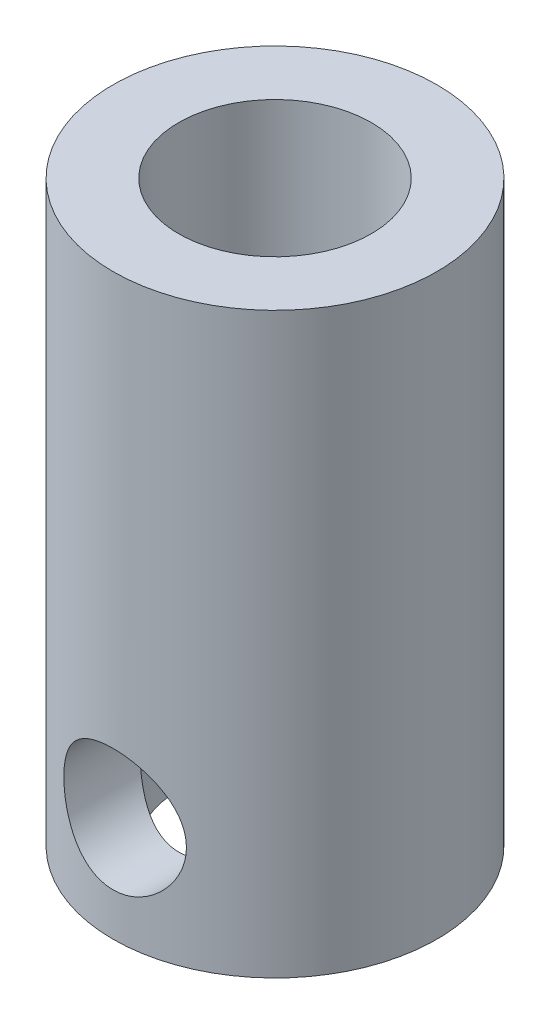
SolidWorks part; units mm, degrees
ref_plane "Front Plane" through (0, 0, 0) normal (0, 0, 1) x (1, 0, 0)
ref_plane "Top Plane" through (0, 0, 0) normal (0, 1, 0) x (1, 0, 0)
ref_plane "Right Plane" through (0, 0, 0) normal (1, 0, 0) x (0, 0, -1)
sketch "Sketch1" plane through (0, 0, 0) normal (0, 0, 1) x (1, 0, 0)
  line L0 (5.334, 19.05) -> (0, 19.05)
  line L1 (0, 19.05) -> (0, 0)
  line L2 (0, 0) -> (5.334, 0)
  line L3 (5.334, 0) -> (5.334, 19.05)
  line L4 (0, 19.05) -> (0, 0) construction
revolve "Revolve1" add sketch "Sketch1" angle 360 about L4
hole_wizard "1/4 (0.25) Diameter Hole1" positions "Sketch3" profile "Sketch2" hole size "1/4" standard "ANSI Inch"
sketch "Sketch3" plane through (0, 0, 0) normal (0, -1, 0) x (-1, 0, 0)
  point P0 (0, 0)
sketch "Sketch2" plane through (0, 0, 0) normal (1, 0, 0) x (0, 0, -1)
  line L0 (0, 0) -> (0, 19.05)
  line L1 (0, 19.05) -> (3.175, 19.05)
  line L2 (3.175, 19.05) -> (3.175, 0)
  line L5 (3.175, 0) -> (0, 0)
  line L11 (0, -6.35) -> (0, 107.95) construction
  dimension "Thru Hole Dia." = 6.35
  dimension "Thru Hole Depth" = 19.05
hole_wizard "#21 (0.159) Diameter Hole1" positions "3DSketch1" profile "Sketch4" hole size "#21" standard "ANSI Inch"
sketch3d "3DSketch1"
  point P0 (0, 3.429, 5.334)
  point P1 (0, 15.621, 5.334)
sketch "Sketch4" plane through (0, 3.429, 5.334) normal (1, 0, 0) x (0, -1, 0)
  line L0 (0, 0) -> (0, 2.159)
  line L1 (0, 2.159) -> (2.0193, 2.159)
  line L2 (2.0193, 2.159) -> (2.0193, 0)
  line L5 (2.0193, 0) -> (0, 0)
  line L11 (0, -6.35) -> (0, 107.95) construction
  dimension "Thru Hole Dia." = 4.0386
  dimension "Thru Hole Depth" = 2.159
